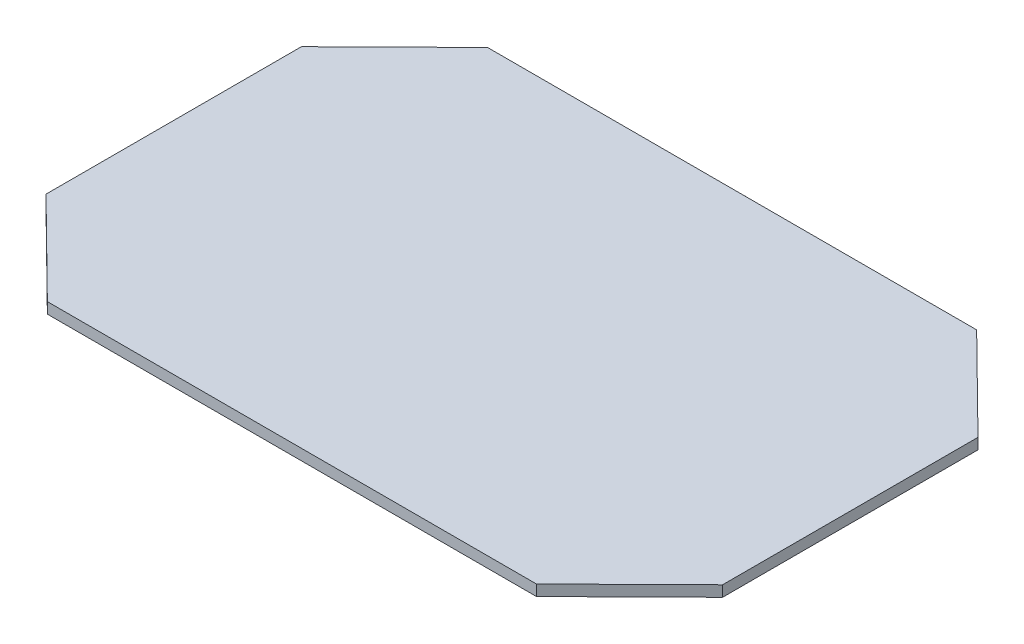
SolidWorks part; units mm, degrees
ref_plane "Alzado" through (0, 0, 0) normal (0, 0, 1) x (1, 0, 0)
ref_plane "Planta" through (0, 0, 0) normal (0, 1, 0) x (1, 0, 0)
ref_plane "Vista lateral" through (0, 0, 0) normal (1, 0, 0) x (0, 0, -1)
sketch "Croquis1" plane through (0, 0, 0) normal (0, 1, 0) x (1, 0, 0)
  line L0 (-90, 81) -> (-124.5, 47)
  line L1 (-124.5, 47) -> (-124.5, 81) construction
  line L2 (-124.5, -47) -> (-124.5, 47)
  line L3 (-124.5, 81) -> (-90, 81) construction
  line L4 (124.5, -47) -> (124.5, 47)
  line L5 (0, 0) -> (103.719, 67.4798) construction
  line L6 (-103.719, 67.4798) -> (0, 0) construction
  line L7 (124.5, 47) -> (90, 81)
  line L8 (0, 0) -> (124.5, 0) construction
  line L9 (0, 0) -> (0, 103.6098) construction
  line L10 (90, 81) -> (124.5, 81) construction
  line L11 (-90, 81) -> (0, 81)
  line L12 (0, 81) -> (90, 81)
  line L13 (124.5, 81) -> (124.5, 47) construction
  line L14 (124.5, -47) -> (90, -81)
  line L15 (-90, -81) -> (0, -81)
  line L16 (-90, -81) -> (-124.5, -47)
  line L17 (0, -81) -> (90, -81)
  point P0 (0, 0)
  point P20 (-124.5, 0)
  dimension "D3" = 180
  dimension "D4" = 47
  dimension "D5" = 47
extrude "Saliente-Extruir1" add sketch "Croquis1" along normal blind 4
